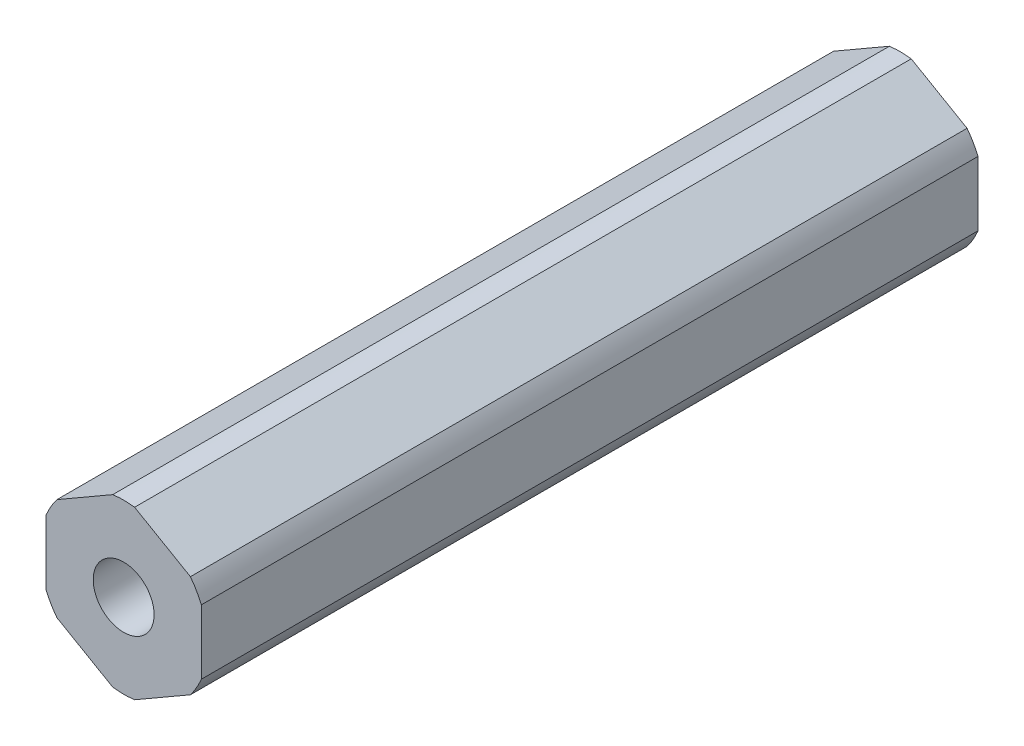
SolidWorks part; units mm, degrees
ref_plane "Front Plane" through (0, 0, 0) normal (0, 0, 1) x (1, 0, 0)
ref_plane "Top Plane" through (0, 0, 0) normal (0, 1, 0) x (1, 0, 0)
ref_plane "Right Plane" through (0, 0, 0) normal (1, 0, 0) x (0, 0, -1)
sketch "Sketch1" plane through (0, 0, 0) normal (0, 0, 1) x (1, 0, 0)
  line L0 (0, 7.3323) -> (-0.893, 6.8168) construction
  line L1 (-0.893, 6.8168) -> (-5.457, 4.1818)
  line L2 (-6.35, 2.635) -> (-6.35, -2.635)
  line L3 (-5.457, -4.1818) -> (-0.893, -6.8168)
  line L4 (0.893, -6.8168) -> (5.457, -4.1818)
  line L5 (6.35, -2.635) -> (6.35, 2.635)
  line L6 (5.457, 4.1818) -> (0.893, 6.8168)
  line L7 (0.893, 6.8168) -> (0, 7.3323) construction
  circle A0 centre (0, 0) radius 6.35 construction
  arc A2 (-6.35, -2.635) -> (-5.457, -4.1818) centre (0, 0) ccw
  arc A3 (-5.457, 4.1818) -> (-6.35, 2.635) centre (0, 0) ccw
  arc A4 (0.893, 6.8168) -> (-0.893, 6.8168) centre (0, 0) ccw
  arc A5 (-0.893, -6.8168) -> (0.893, -6.8168) centre (0, 0) ccw
  arc A6 (5.457, -4.1818) -> (6.35, -2.635) centre (0, 0) ccw
  arc A7 (6.35, 2.635) -> (5.457, 4.1818) centre (0, 0) ccw
  dimension "D1" = 12.7
  dimension "D2" = 13.75
extrude "Boss-Extrude1" add sketch "Sketch1" along normal mid plane 63.5
sketch "Sketch3" plane through (0, 0, 31.75) normal (0, 0, 1) x (1, 0, 0)
  circle A0 centre (0, 0) radius 2.4892
  dimension "D1" = 4.9784
extrude "Cut-Extrude1" cut sketch "Sketch3" against normal through all
